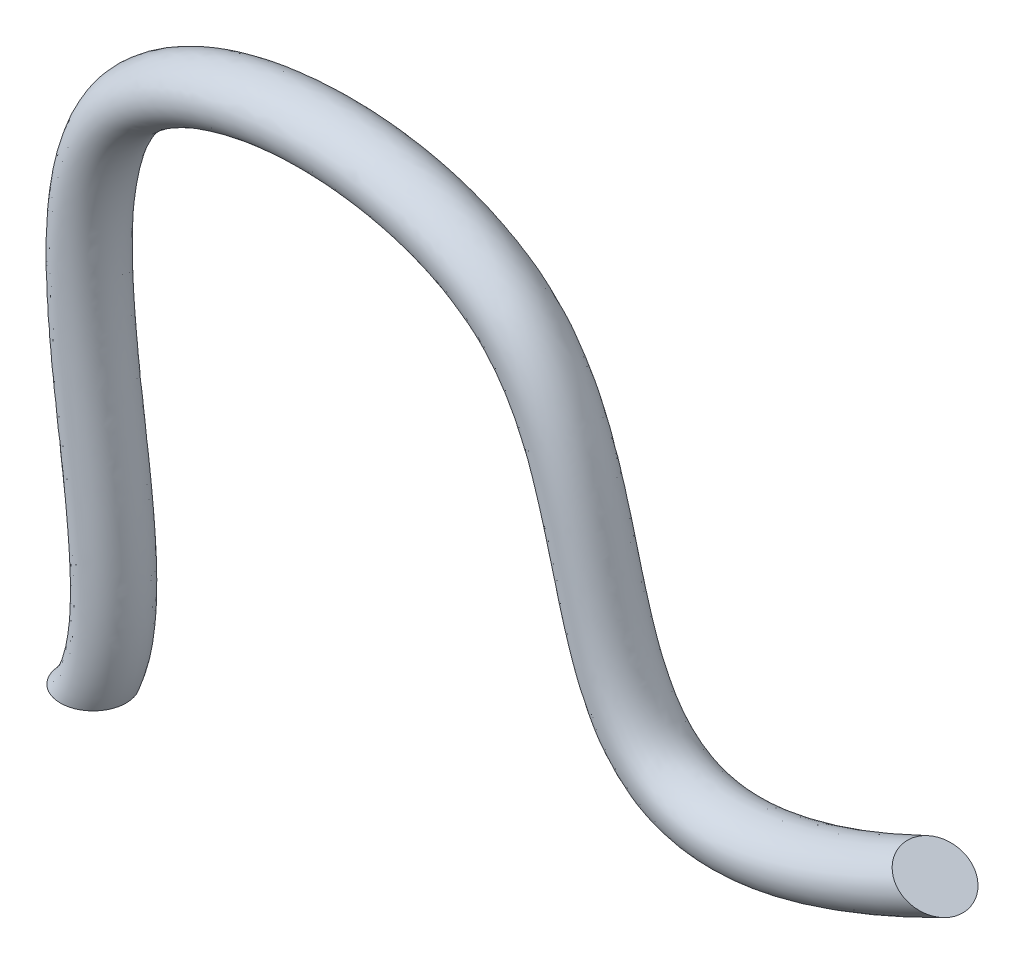
SolidWorks part; units mm, degrees
ref_plane "Front Plane" through (0, 0, 0) normal (0, 0, 1) x (1, 0, 0)
ref_plane "Top Plane" through (0, 0, 0) normal (0, 1, 0) x (1, 0, 0)
ref_plane "Right Plane" through (0, 0, 0) normal (1, 0, 0) x (0, 0, -1)
sketch "Sketch3" plane through (0, 0, 0) normal (0, 0, 1) x (1, 0, 0)
  spline S0 degree 3 poles (0, 0) (7.9927, 13.1521) (-19.8028, 70.7268) (75.194, 72.2058) (50.4188, 6.3093) (97.6892, 29.5062) knots 0 0 0 0 0.355439 0.614638 1 1 1 1
sketch "Sketch6" plane through (0, 0, 0) normal (0, 1, 0) x (1, 0, 0)
  circle A0 centre (0, 0) radius 3.81
  dimension "D1" = 7.62
sweep "Sweep2" add profiles "Sketch6" path "Sketch3"
